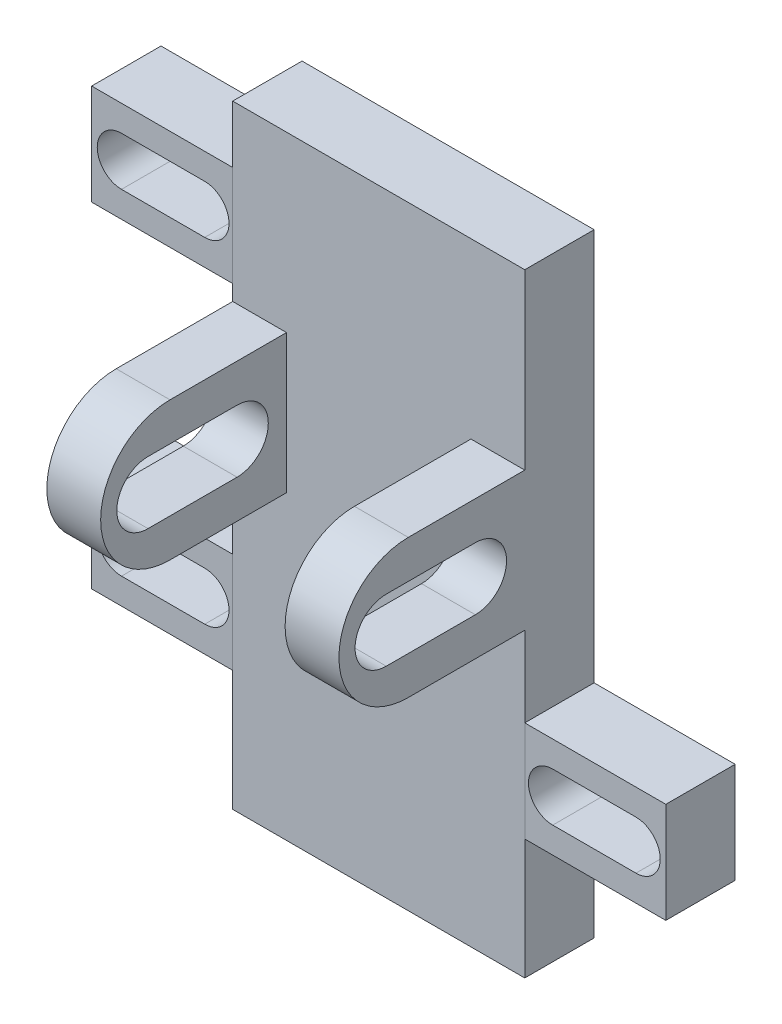
SolidWorks part; units mm, degrees
ref_plane "Front Plane" through (0, 0, 0) normal (0, 0, 1) x (1, 0, 0)
ref_plane "Top Plane" through (0, 0, 0) normal (0, 1, 0) x (1, 0, 0)
ref_plane "Right Plane" through (0, 0, 0) normal (1, 0, 0) x (0, 0, -1)
sketch "Sketch1" plane through (0, 0, 0) normal (0, 0, 1) x (1, 0, 0)
  line L0 (4692.3212, -62.8445) -> (4650.9212, -62.8445) construction
  line L1 (4661.0828, -18.6148) -> (4682.1433, -18.6148)
  line L2 (4661.0828, -18.6148) -> (4661.0828, -62.8445)
  line L3 (4661.0828, -62.8445) -> (4682.1433, -62.8445)
  line L4 (4682.1433, -18.6148) -> (4682.1433, -62.8445)
  line L5 (4661.0828, -27.1456) -> (4658.9212, -27.1456) construction
  line L6 (4658.9212, -12.4285) -> (4658.9212, -50.5381) construction
  line L7 (4682.1433, -34.3161) -> (4684.3037, -34.2412) construction
  line L8 (4684.3037, -50.5381) -> (4684.3037, -12.4285) construction
extrude "Boss-Extrude1" add sketch "Sketch1" along normal blind 5
sketch "Sketch2" plane through (0, 0, 0) normal (0, 0, -1) x (-1, 0, 0)
  line L0 (-4671.6212, -59.6913) -> (-4671.6212, -53.6913) construction
  line L1 (-4664.1212, -59.6913) -> (-4679.1212, -59.6913) construction
  line L2 (-4679.1212, -53.6913) -> (-4664.1212, -53.6913) construction
  line L4 (-4674.1212, -53.8163) -> (-4669.1212, -53.8163)
  line L5 (-4674.1212, -53.8163) -> (-4674.1212, -59.5663)
  line L6 (-4674.1212, -59.5663) -> (-4669.1212, -59.5663)
  line L7 (-4669.1212, -53.8163) -> (-4669.1212, -59.5663)
  line L8 (-4674.1212, -53.8163) -> (-4669.1212, -59.5663) construction
  line L9 (-4674.1212, -59.5663) -> (-4669.1212, -53.8163) construction
  point P6 (-4671.6212, -56.6913)
  dimension "D1" = 5.75
  dimension "D2" = 5
extrude "Boss-Extrude2" add sketch "Sketch2" along normal blind 8
sketch "Sketch4" plane through (4661.0828, 0, 0) normal (-1, 0, 0) x (0, 0, 1)
  line L3 (5, -18.6148) -> (5, -62.8445) construction
  line L4 (13.4005, -31.1292) -> (5, -31.1292)
  line L6 (13.4005, -41.1292) -> (5, -41.1292)
  line L7 (5, -31.1292) -> (5, -41.1292)
  arc A0 (13.4005, -41.1292) -> (13.4005, -31.1292) centre (13.4005, -36.1292) ccw
  dimension "D1" = 5
extrude "Boss-Extrude3" add sketch "Sketch4" against normal blind 3.8801
sketch "Sketch5" plane through (4664.9629, 0, 0) normal (1, 0, 0) x (0, 0, -1)
  line L0 (-14.9864, -36.1292) -> (-8.5634, -36.1292) construction
  line L1 (-14.9864, -33.8792) -> (-8.5634, -33.8792)
  line L2 (-14.9864, -38.3792) -> (-8.5634, -38.3792)
  line L3 (-13.4005, -36.1292) -> (-8.9343, -36.1292) construction
  arc A1 (-14.9864, -33.8792) -> (-14.9864, -38.3792) centre (-14.9864, -36.1292) ccw
  arc A2 (-8.5634, -38.3792) -> (-8.5634, -33.8792) centre (-8.5634, -36.1292) ccw
  point P3 (-11.7749, -36.1292)
  dimension "D1" = 2.25
  dimension "D2" = 1.6257
  dimension "D3" = 4.8372
extrude "Cut-Extrude1" cut sketch "Sketch5" against normal blind 8
ref_plane "Plane1" through (4671.6131, 0, 0) normal (-1, 0, 0) x (0, 0, 1)
mirror "Mirror2" about plane through (4671.6131, 0, 0) normal (-1, 0, 0) of "Cut-Extrude1", "Boss-Extrude3"
sketch "Sketch6" plane through (0, 0, 5) normal (0, 0, 1) x (1, 0, 0)
  line L0 (4688.3131, -48.9131) -> (4688.3131, -52.1631) construction
  line L1 (4682.1433, -46.9131) -> (4692.3131, -46.9131)
  line L2 (4682.1433, -46.9131) -> (4682.1433, -54.1631)
  line L3 (4682.1433, -54.1631) -> (4692.3131, -54.1631)
  line L4 (4692.3131, -46.9131) -> (4692.3131, -54.1631)
  line L5 (4658.9131, -50.5381) -> (4684.2955, -50.5381) construction
  line L6 (4688.3131, -52.1631) -> (4688.3131, -54.1631) construction
  line L7 (4688.3131, -48.9131) -> (4688.3131, -46.9131) construction
  line L9 (4690.1601, -50.5384) -> (4684.1601, -50.5381) construction
  line L10 (4690.16, -52.2884) -> (4684.16, -52.2881)
  line L11 (4690.1602, -48.7884) -> (4684.1602, -48.7881)
  line L12 (4686.6881, -50.5381) -> (4689.9381, -50.5381) construction
  arc A1 (4690.16, -52.2884) -> (4690.1602, -48.7884) centre (4690.1601, -50.5384) ccw
  arc A2 (4684.1602, -48.7881) -> (4684.16, -52.2881) centre (4684.1601, -50.5381) ccw
  circle A3 centre (4688.3131, -50.5381) radius 1.625 construction
  point P4 (0, 0)
  point P5 (4689.9381, -50.5381)
  point P6 (0, 0)
  point P7 (4689.9381, -50.5381)
  point P10 (4686.6881, -50.5381)
  point P18 (4687.1601, -50.5382)
  point P24 (4686.6881, -50.5381)
  point P25 (4684.1601, -50.5381)
  dimension "D2" = 6
  dimension "D1" = 1.75
extrude "Boss-Extrude4" add sketch "Sketch6" against normal blind 5 separate body
ref_plane "Plane2" through (4671.6131, 0, 0) normal (-1, 0, 0) x (0, 0, 1)
mirror "Mirror3" about plane through (4671.6131, 0, 0) normal (-1, 0, 0) of bodies 107
ref_plane "Plane3" through (0, -24.872, 0) normal (0, -1, 0) x (-1, 0, 0)
sketch "Sketch9" plane through (0, 0, 5) normal (0, 0, 1) x (1, 0, 0)
  line L0 (4671.6131, -62.8445) -> (4671.6131, -18.6148) construction
  line L1 (4661.0828, -62.8445) -> (4682.1433, -62.8445) construction
  line L2 (4682.1433, -18.6148) -> (4661.0828, -18.6148) construction
  line L3 (4671.6131, -40.7297) -> (4677.5932, -40.7297) construction
  point P8 (0, 0)
ref_plane "Plane4" through (0, -40.7297, 0) normal (0, -1, 0) x (-1, 0, 0)
sketch "Sketch10" plane through (0, 0, 5) normal (0, 0, 1) x (1, 0, 0)
  line L0 (4654.9131, -26.3852) -> (4654.9131, -50.5381) construction
  line L1 (4654.9131, -38.4617) -> (4652.351, -38.4617) construction
ref_plane "Plane5" through (0, -38.4617, 0) normal (0, -1, 0) x (-1, 0, 0)
mirror "Mirror4" about plane through (0, -38.4617, 0) normal (0, -1, 0) of bodies 109 107
sketch "Sketch11" plane through (0, 0, 5) normal (0, 0, 1) x (1, 0, 0)
  line L1 (4682.1433, -22.7602) -> (4692.3131, -22.7602)
  line L2 (4682.1433, -22.7602) -> (4682.1433, -30.0102)
  line L3 (4682.1433, -30.0102) -> (4692.3131, -30.0102)
  line L4 (4692.3131, -22.7602) -> (4692.3131, -30.0102)
extrude "Cut-Extrude2" cut sketch "Sketch11" against normal up to vertex (5 mm away) up to point (4682.1433, -22.7602, 0)
